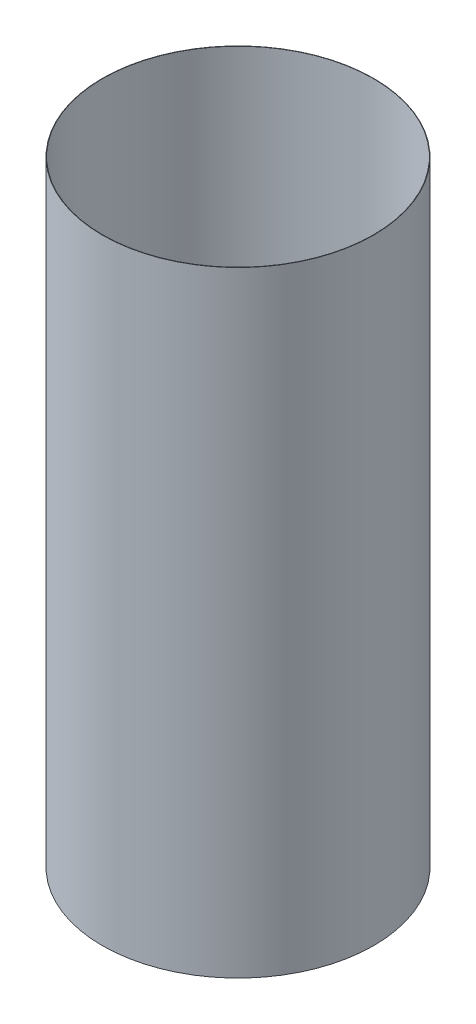
SolidWorks part; units mm, degrees
ref_plane "Front Plane" through (0, 0, 0) normal (0, 0, 1) x (1, 0, 0)
ref_plane "Top Plane" through (0, 0, 0) normal (0, 1, 0) x (1, 0, 0)
ref_plane "Right Plane" through (0, 0, 0) normal (1, 0, 0) x (0, 0, -1)
sketch "Sketch1" plane through (0, 0, 0) normal (0, 1, 0) x (1, 0, 0)
  circle A0 centre (0, 0) radius 23.8125
  circle A1 centre (0, 0) radius 23.749
  dimension "D1" = 47.625
  dimension "D2" = 47.498
extrude "Boss-Extrude1" add sketch "Sketch1" along normal blind 107.95
